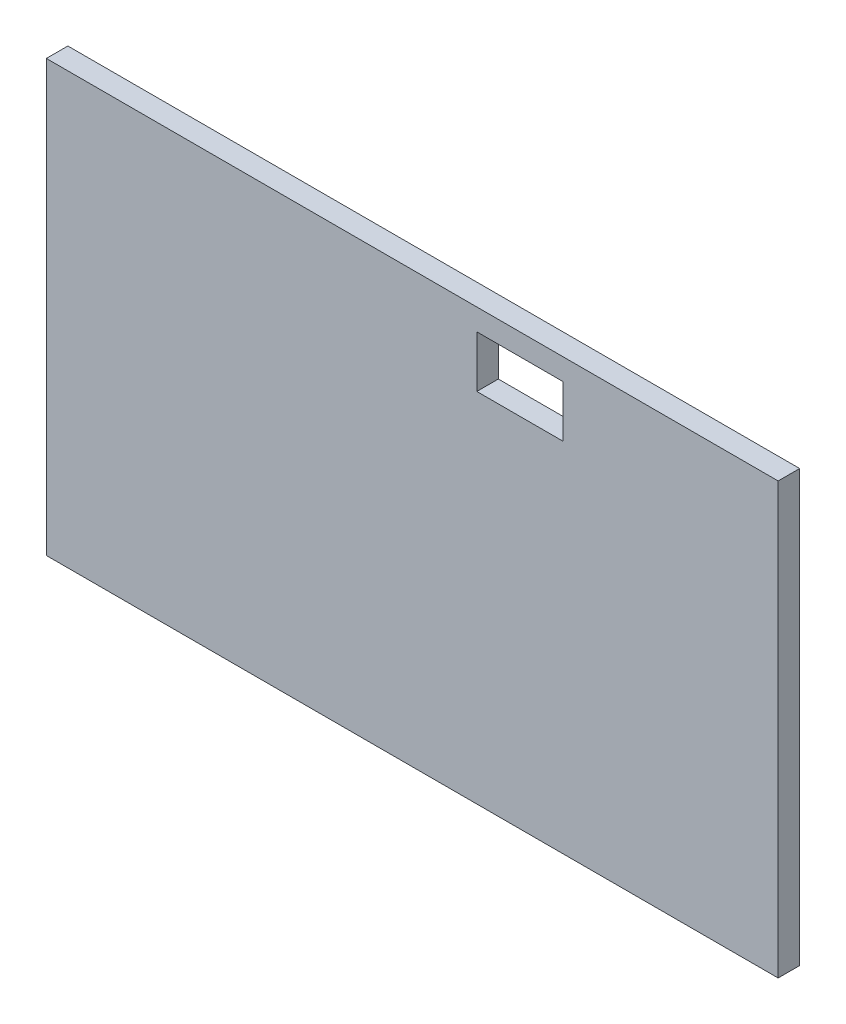
SolidWorks part; units mm, degrees
ref_plane "Спереди" through (0, 0, 0) normal (0, 0, 1) x (1, 0, 0)
ref_plane "Сверху" through (0, 0, 0) normal (0, 1, 0) x (1, 0, 0)
ref_plane "Справа" through (0, 0, 0) normal (1, 0, 0) x (0, 0, -1)
sketch "Эскиз1" plane through (0, 0, 0) normal (0, 0, 1) x (1, 0, 0)
  line L0 (0, 0) -> (170, 0)
  line L1 (170, 0) -> (170, 100)
  line L2 (170, 100) -> (0, 100)
  line L3 (0, 100) -> (0, 0)
  line L5 (100, 83) -> (120, 83)
  line L6 (100, 83) -> (100, 95)
  line L7 (100, 95) -> (120, 95)
  line L8 (120, 83) -> (120, 95)
  line L9 (100, 83) -> (120, 95) construction
  line L10 (100, 95) -> (120, 83) construction
  point P3 (110, 89)
  dimension "D1" = 100
  dimension "D2" = 170
  dimension "D3" = 5
  dimension "D4" = 20
  dimension "D5" = 12
  dimension "D6" = 50
extrude "Бобышка-Вытянуть1" add sketch "Эскиз1" along normal blind 5
